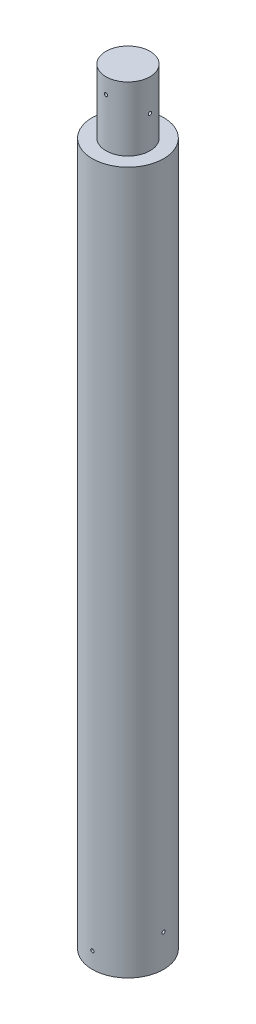
SolidWorks part; units mm, degrees
ref_plane "Front Plane" through (0, 0, 0) normal (0, 0, 1) x (1, 0, 0)
ref_plane "Top Plane" through (0, 0, 0) normal (0, 1, 0) x (1, 0, 0)
ref_plane "Right Plane" through (0, 0, 0) normal (1, 0, 0) x (0, 0, -1)
sketch "Sketch1" plane through (0, 0, 0) normal (0, 1, 0) x (1, 0, 0)
  circle A0 centre (0, 0) radius 11
extrude "Boss-Extrude1" add sketch "Sketch1" along normal blind 216.6667 contours A0
sketch "Sketch2" plane through (0, 0, 0) normal (0, 1, 0) x (1, 0, 0)
  circle A0 centre (0, 0) radius 6.8
extrude "Boss-Extrude2" add sketch "Sketch2" along normal blind 19.8 from offset 216.6667
sketch "Sketch3" plane through (0, 0, 0) normal (0, 0, 1) x (1, 0, 0)
  circle A0 centre (0, 231.6667) radius 0.5
  point P5 (0, 0)
extrude "Cut-Extrude1" cut sketch "Sketch3" against normal blind 9 from offset 1.44 offset against normal yes
mirror "Mirror1" about plane through (0, 0, 0) normal (0, 0, 1) of "Cut-Extrude1"
sketch "Sketch4" plane through (0, 0, 0) normal (1, 0, 0) x (0, 0, -1)
  line L2 (0, 12.1) -> (0, -12.1) construction
  circle A0 centre (0, 226.6667) radius 0.5
extrude "Cut-Extrude2" cut sketch "Sketch4" against normal blind 9 from offset 1.4 offset against normal yes
mirror "Mirror2" about plane through (0, 0, 0) normal (1, 0, 0) of "Cut-Extrude2"
sketch "Sketch6" plane through (0, 0, 0) normal (0, 1, 0) x (1, 0, 0)
  circle A0 centre (0, 0) radius 7
extrude "Cut-Extrude3" cut sketch "Sketch6" along normal blind 20
sketch "Sketch7" plane through (0, 0, 0) normal (1, 0, 0) x (0, 0, -1)
  line L1 (0, 12.1) -> (0, -12.1) construction
  circle A0 centre (0, 10) radius 0.5
extrude "Cut-Extrude4" cut sketch "Sketch7" against normal through all both and the other way through all
sketch "Sketch10" plane through (0, 0, 0) normal (0, 0, 1) x (1, 0, 0)
  line L1 (0, -12.1) -> (0, 12.1) construction
  circle A0 centre (0, 5) radius 0.5
extrude "Cut-Extrude5" cut sketch "Sketch10" against normal through all both and the other way through all
equation "\"V\"=0"
